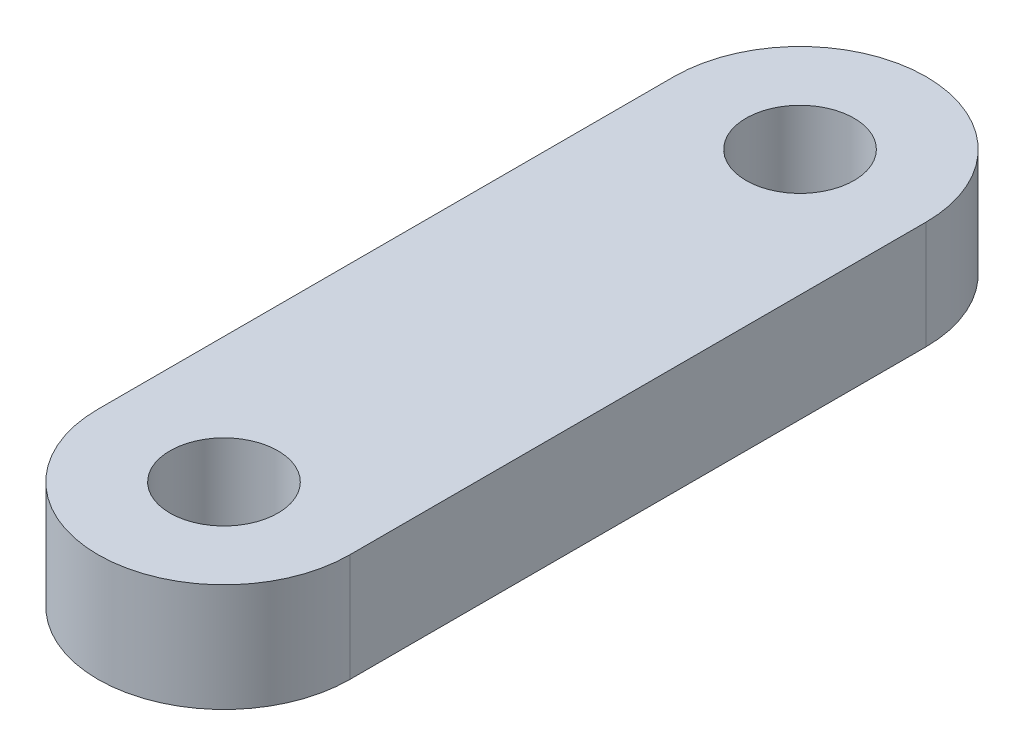
SolidWorks part; units mm, degrees
ref_plane "前视基准面" through (0, 0, 0) normal (0, 0, 1) x (1, 0, 0)
ref_plane "上视基准面" through (0, 0, 0) normal (0, 1, 0) x (1, 0, 0)
ref_plane "右视基准面" through (0, 0, 0) normal (1, 0, 0) x (0, 0, -1)
sketch "草图1" plane through (0, 0, 0) normal (0, 1, 0) x (1, 0, 0)
  line L0 (0, -8) -> (0, 8) construction
  line L1 (-3.5, -8) -> (-3.5, 8)
  line L2 (3.5, -8) -> (3.5, 8)
  arc A0 (-3.5, -8) -> (3.5, -8) centre (0, -8) ccw
  arc A1 (3.5, 8) -> (-3.5, 8) centre (0, 8) ccw
  point P3 (0, 0)
  dimension "D2" = 3.5
  dimension "D1" = 16
extrude "凸台-拉伸1" add sketch "草图1" along normal blind 3
sketch "草图2" plane through (0, 3, 0) normal (0, 1, 0) x (1, 0, 0)
  circle A0 centre (0, 8) radius 1.5
  circle A1 centre (0, -8) radius 1.5
  arc A2 (-3.5, -8) -> (3.5, -8) centre (0, -8) ccw construction
  arc A3 (3.5, 8) -> (-3.5, 8) centre (0, 8) ccw construction
  dimension "D1" = 3
extrude "切除-拉伸1" cut sketch "草图2" against normal blind 3
